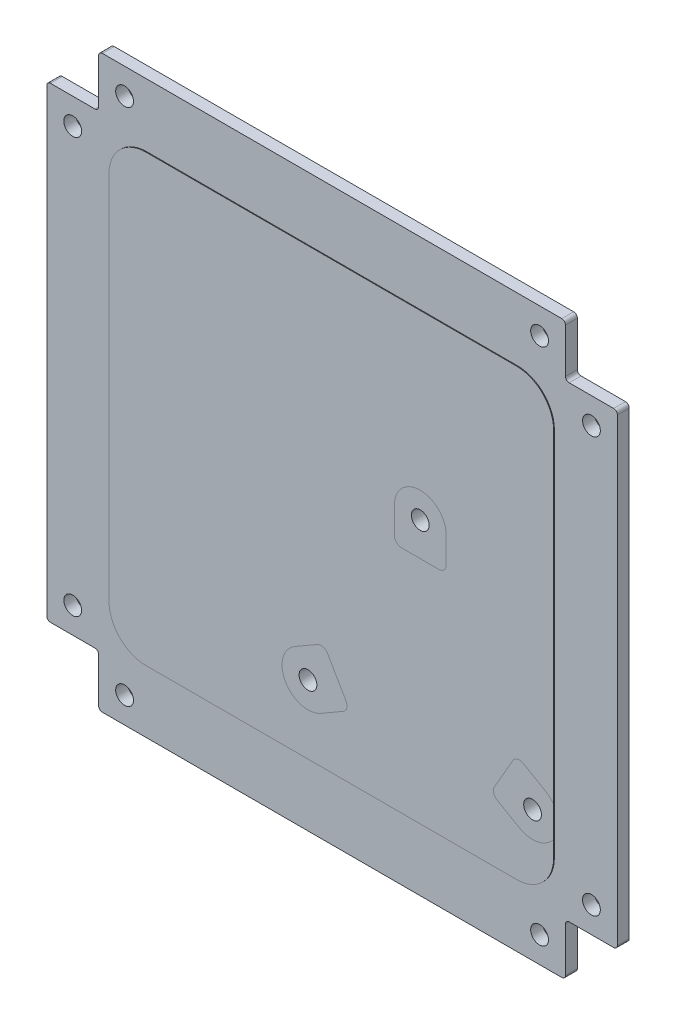
SolidWorks part; units mm, degrees
material "PET"
ref_plane "Front Plane" through (0, 0, 0) normal (0, 0, 1) x (1, 0, 0)
ref_plane "Top Plane" through (0, 0, 0) normal (0, 1, 0) x (1, 0, 0)
ref_plane "Right Plane" through (0, 0, 0) normal (1, 0, 0) x (0, 0, -1)
sketch "Sketch1" plane through (0, 0, 0) normal (0, 0, 1) x (1, 0, 0)
  line L0 (-31.5, 38) -> (-31.5, 32)
  line L1 (-31, -38.5) -> (31, -38.5)
  line L2 (-38.5, 31) -> (-38.5, -31)
  line L3 (-31, 38.5) -> (31, 38.5)
  line L4 (38.5, -31) -> (38.5, 31)
  line L5 (31.5, -38) -> (31.5, -32)
  line L6 (32, -31.5) -> (38, -31.5)
  line L7 (-32, 31.5) -> (-38, 31.5)
  line L8 (31.5, 38) -> (31.5, 32)
  line L9 (32, 31.5) -> (38, 31.5)
  line L10 (-38, -31.5) -> (-32, -31.5)
  line L11 (-31.5, -32) -> (-31.5, -38)
  line L12 (-32, -32) -> (32, 32) construction
  line L13 (32, -32) -> (-32, 32) construction
  arc A0 (-31, 38.5) -> (-31.5, 38) centre (-31, 38) ccw
  arc A1 (31, 38.5) -> (31.5, 38) centre (31, 38) cw
  arc A2 (31.5, 32) -> (32, 31.5) centre (32, 32) ccw
  arc A3 (38, 31.5) -> (38.5, 31) centre (38, 31) cw
  arc A4 (31, -38.5) -> (31.5, -38) centre (31, -38) ccw
  arc A5 (32, -31.5) -> (31.5, -32) centre (32, -32) ccw
  arc A6 (38, -31.5) -> (38.5, -31) centre (38, -31) ccw
  arc A7 (-31.5, -38) -> (-31, -38.5) centre (-31, -38) ccw
  arc A8 (-31.5, -32) -> (-32, -31.5) centre (-32, -32) ccw
  arc A9 (-38.5, -31) -> (-38, -31.5) centre (-38, -31) ccw
  arc A10 (-38, 31.5) -> (-38.5, 31) centre (-38, 31) ccw
  arc A11 (-32, 31.5) -> (-31.5, 32) centre (-32, 32) ccw
  point P0 (0, 0)
  dimension "D4" = 0.5
  dimension "D1" = 7
  dimension "D2" = 7
  dimension "D3" = 7
  dimension "D5" = 7
  dimension "D6" = 7
  dimension "D7" = 7
  dimension "D8" = 7
  dimension "D9" = 7
  dimension "D10" = 77
  dimension "D11" = 77
extrude "Boss-Extrude1" add sketch "Sketch1" along normal blind 1.6
sketch "Esboço1" plane through (0, 0, 1.6) normal (0, 0, 1) x (1, 0, 0)
  line L1 (-25, -30) -> (25, -30)
  line L2 (-30, -25) -> (-30, 25)
  line L3 (-25, 30) -> (25, 30)
  line L4 (30, -25) -> (30, 25)
  line L5 (-25, -25) -> (25, 25) construction
  line L6 (-25, 25) -> (25, -25) construction
  arc A0 (-30, 25) -> (-25, 30) centre (-25, 25) cw
  arc A1 (25, 30) -> (30, 25) centre (25, 25) cw
  arc A2 (30, -25) -> (25, -30) centre (25, -25) cw
  arc A3 (-25, -30) -> (-30, -25) centre (-25, -25) cw
  point P0 (0, 0)
  dimension "D1" = 5
  dimension "D2" = 60
  dimension "D3" = 60
extrude "Boss-Extrude2" add sketch "Esboço1" along normal blind 0.1
hole_wizard "M2 Hole1-FixingStructure" positions "Sketch3" profile "Sketch2" hole size "M2" standard "DIN"
sketch "Sketch3" plane through (0, 0, 0) normal (0, 0, -1) x (-1, 0, 0)
  line L0 (-31, 38.5) -> (31, 38.5) construction
  line L1 (31, -38.5) -> (-31, -38.5) construction
  line L2 (-38.5, -31) -> (-38.5, 31) construction
  line L3 (38.5, 31) -> (38.5, -31) construction
  line L4 (-31, 38.5) -> (31, 38.5) construction
  line L5 (31, -38.5) -> (-31, -38.5) construction
  line L6 (38.5, 31) -> (38.5, -31) construction
  line L7 (-38.5, -31) -> (-38.5, 31) construction
  point P0 (-28, 35)
  point P2 (28, 35)
  point P4 (-28, -35)
  point P6 (28, -35)
  point P20 (35, 28)
  point P22 (35, -28)
  point P24 (-35, -28)
  point P26 (-35, 28)
  dimension "D1" = 3.5
  dimension "D2" = 3.5
  dimension "D3" = 10.5
  dimension "D4" = 10.5
  dimension "D5" = 10.5
  dimension "D6" = 10.5
  dimension "D7" = 3.5
  dimension "D8" = 3.5
sketch "Sketch2" plane through (28, 35, 0) normal (1, 0, 0) x (0, 1, 0)
  line L0 (0, 0) -> (0, 200.721)
  line L1 (0, 200.721) -> (1.2, 200)
  line L2 (1.2, 200) -> (1.2, 0)
  line L5 (1.2, 0) -> (0, 0)
  line L10 (0, 200.721) -> (-1.2, 200) construction
  line L11 (0, -6.35) -> (0, 107.95) construction
  dimension "Hole Dia." = 2.4
  dimension "Hole Depth" = 200
  dimension "Drill Angle" = 118
sketch "Sketch5" plane through (0, 0, 1.7) normal (0, 0, 1) x (1, 0, 0)
  circle A0 centre (-3.1554, -20.75) radius 1.2 construction
  circle A1 centre (27.1554, -20.75) radius 1.2 construction
  circle A2 centre (12, 5.5) radius 1.2 construction
  circle A3 centre (-3.1554, -20.75) radius 1.2
  circle A4 centre (27.1554, -20.75) radius 1.2
  circle A5 centre (12, 5.5) radius 1.2
extrude "Cut-Extrude1" cut sketch "Sketch5" against normal up to surface (1.7 mm away) up to face at (26.8, 35, 0)
sketch "Sketch6" plane through (0, 0, 1.7) normal (0, 0, 1) x (1, 0, 0)
  line L0 (1.6256, -22.0311) -> (-1.4054, -23.7811)
  line L1 (-4.9054, -17.7189) -> (-1.8744, -15.9689)
  line L2 (-0.5083, -16.3349) -> (1.9917, -20.6651)
  line L3 (8.5, 2) -> (8.5, 5.5)
  line L4 (15.5, 5.5) -> (15.5, 2)
  line L5 (14.5, 1) -> (9.5, 1)
  line L6 (26.7404, -16.4689) -> (28.9054, -17.7189)
  line L7 (25.4054, -23.7811) -> (23.2404, -22.5311)
  line L8 (25.8744, -15.9689) -> (28.9054, -17.7189)
  line L9 (25.4054, -23.7811) -> (22.3744, -22.0311)
  line L10 (22.0083, -20.6651) -> (24.5083, -16.3349)
  line L11 (22.0083, -20.6651) -> (24.5083, -16.3349)
  arc A0 (1.6256, -22.0311) -> (1.9917, -20.6651) centre (1.1256, -21.1651) ccw
  arc A1 (-4.9054, -17.7189) -> (-1.4054, -23.7811) centre (-3.1554, -20.75) ccw
  arc A2 (25.8744, -15.9689) -> (24.5083, -16.3349) centre (25.3744, -16.8349) ccw
  arc A3 (25.4054, -23.7811) -> (28.9054, -17.7189) centre (27.1554, -20.75) ccw
  arc A4 (25.4054, -23.7811) -> (28.9054, -17.7189) centre (27.1554, -20.75) ccw
  arc A5 (22.3744, -22.0311) -> (22.0083, -20.6651) centre (22.8744, -21.1651) cw
  circle A6 centre (12, -12) radius 4.1 construction
  arc A7 (-1.8744, -15.9689) -> (-0.5083, -16.3349) centre (-1.3744, -16.8349) cw
  arc A8 (8.5, 2) -> (9.5, 1) centre (9.5, 2) ccw
  arc A9 (15.5, 5.5) -> (8.5, 5.5) centre (12, 5.5) ccw
  arc A10 (15.5, 2) -> (14.5, 1) centre (14.5, 2) cw
  point P13 (12, -12)
  point P36 (12, -12)
  dimension "D3" = 1
  dimension "D1" = 1
  dimension "D2" = 1
  dimension "D4" = 3
split line "Split Line1"
